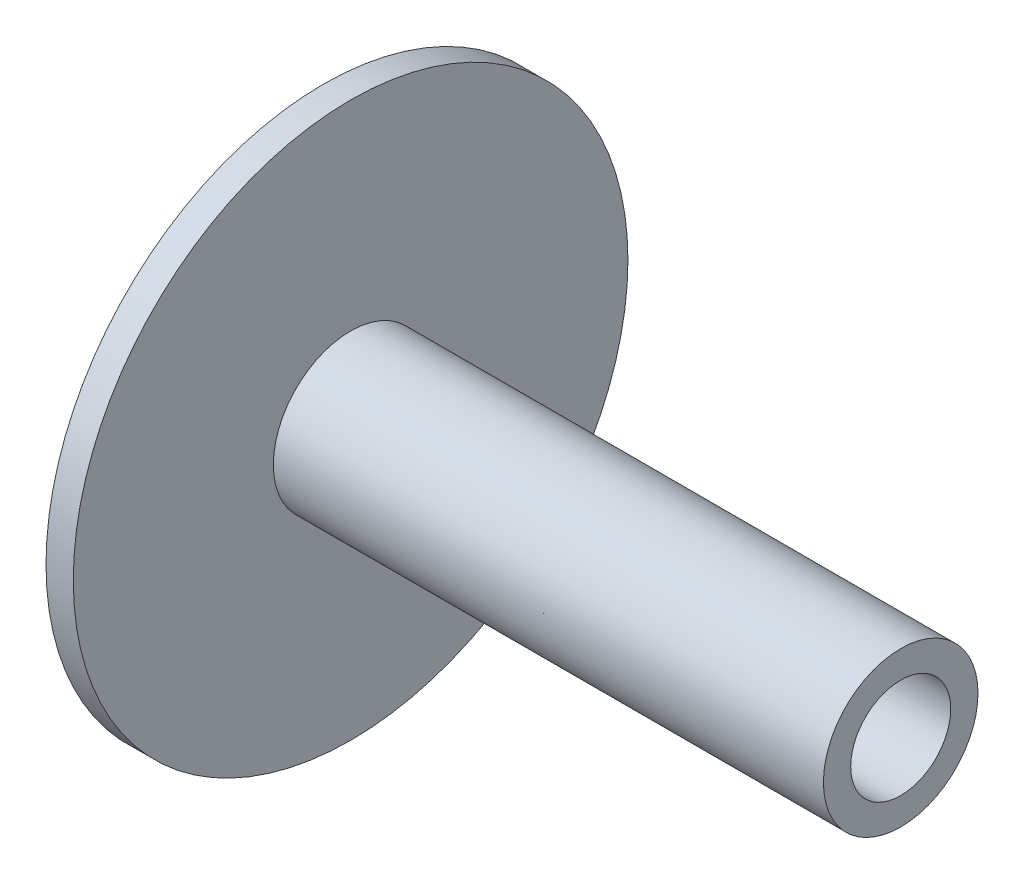
SolidWorks part; units mm, degrees
ref_plane "Front Plane" through (0, 0, 0) normal (0, 0, 1) x (1, 0, 0)
ref_plane "Top Plane" through (0, 0, 0) normal (0, 1, 0) x (1, 0, 0)
ref_plane "Right Plane" through (0, 0, 0) normal (1, 0, 0) x (0, 0, -1)
sketch "Sketch1" plane through (0, 0, 0) normal (1, 0, 0) x (0, 0, -1)
  circle A0 centre (0, 0) radius 2.2
  circle A1 centre (0, 0) radius 3.4
  dimension "D1" = 4.4
  dimension "D2" = 1.2
extrude "Boss-Extrude1" add sketch "Sketch1" along normal blind 24.2
sketch "Sketch3" plane through (0, 0, 0) normal (-1, 0, 0) x (0, 0, 1)
  circle A1 centre (0, 0) radius 12.2
  circle A2 centre (0, 0) radius 2.2
  circle A3 centre (0, 0) radius 2.2
  dimension "D1" = 0
  dimension "D2" = 10
extrude "Boss-Extrude2" add sketch "Sketch3" along normal blind 1.2
sketch "Sketch4"
